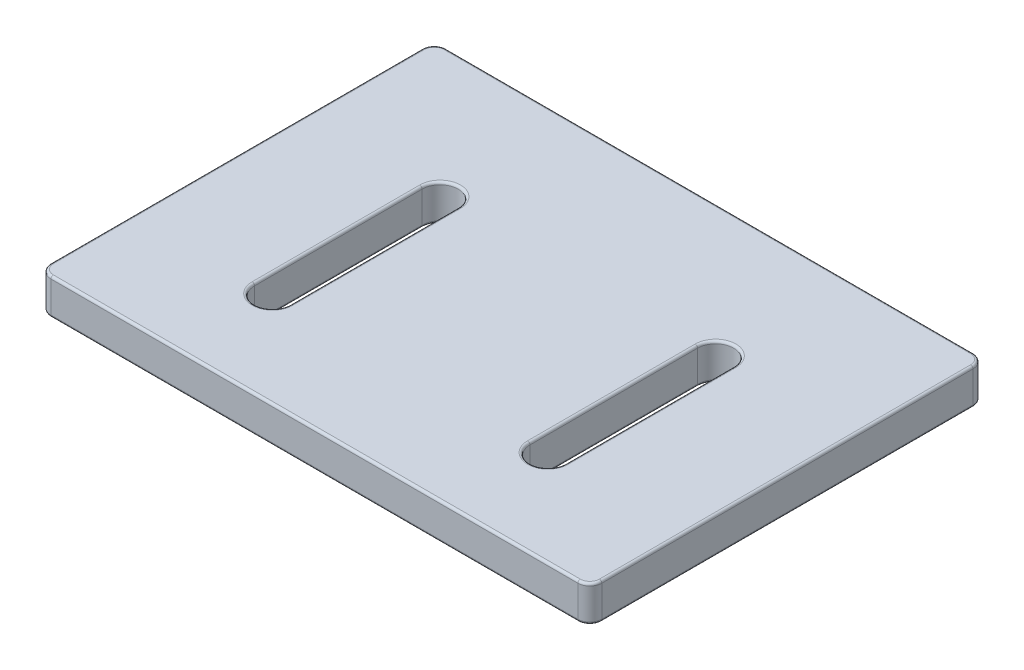
SolidWorks part; units mm, degrees
ref_plane "Front Plane" through (0, 0, 0) normal (0, 0, 1) x (1, 0, 0)
ref_plane "Top Plane" through (0, 0, 0) normal (0, 1, 0) x (1, 0, 0)
ref_plane "Right Plane" through (0, 0, 0) normal (1, 0, 0) x (0, 0, -1)
sketch "Sketch1" plane through (0, 0, 0) normal (0, 1, 0) x (1, 0, 0)
  line L0 (0, 0) -> (0, 33) construction
  line L1 (22, 0) -> (-22, 0)
  line L2 (-23, 1) -> (-23, 32)
  line L3 (-22, 33) -> (22, 33)
  line L4 (-11.5, 22) -> (-11.5, 8) construction
  line L5 (-10, 22) -> (-10, 8)
  line L6 (-13, 22) -> (-13, 8)
  line L7 (23, 1) -> (23, 32)
  line L8 (11.5, 22) -> (11.5, 8) construction
  line L9 (10, 22) -> (10, 8)
  line L10 (13, 22) -> (13, 8)
  arc A0 (-10, 22) -> (-13, 22) centre (-11.5, 22) ccw
  arc A1 (-13, 8) -> (-10, 8) centre (-11.5, 8) ccw
  arc A2 (-22, 0) -> (-23, 1) centre (-22, 1) cw
  arc A3 (-23, 32) -> (-22, 33) centre (-22, 32) cw
  arc A4 (23, 32) -> (22, 33) centre (22, 32) ccw
  arc A5 (22, 0) -> (23, 1) centre (22, 1) ccw
  arc A6 (10, 22) -> (13, 22) centre (11.5, 22) cw
  arc A7 (13, 8) -> (10, 8) centre (11.5, 8) cw
  point P7 (-11.5, 15)
  point P14 (-23, 0)
  point P23 (23, 0)
  point P26 (11.5, 15)
  dimension "D7" = 1
  dimension "D1" = 3
  dimension "D2" = 23
  dimension "D3" = 33
  dimension "D4" = 14
  dimension "D5" = 8
  dimension "D6" = 10
extrude "Boss-Extrude1" add sketch "Sketch1" along normal blind 3
fillet "Fillet1" radius 0.2 32 edges at (11.5, 0, -6.5) (10, 0, -15) (11.5, 0, -23.5) (13, 0, -15) (-11.5, 0, -6.5) (-13, 0, -15) (-11.5, 0, -23.5) (-10, 0, -15) (0, 0, 0) (22.7071, 0, -0.2929) (23, 0, -16.5) (22.7071, 0, -32.7071) (0, 0, -33) (-22.7071, 0, -32.7071) (-23, 0, -16.5) (-22.7071, 0, -0.2929) (10, 3, -15) (11.5, 3, -6.5) (13, 3, -15) (11.5, 3, -23.5) (-23, 3, -16.5) (-22.7071, 3, -32.7071) (0, 3, -33) (22.7071, 3, -32.7071) (23, 3, -16.5) (22.7071, 3, -0.2929) (0, 3, 0) (-22.7071, 3, -0.2929) (-13, 3, -15) (-11.5, 3, -6.5) (-10, 3, -15) (-11.5, 3, -23.5)
ref_plane "Plane1" through (0, 0, -22) normal (0, 0, 1) x (0, -1, 0)
